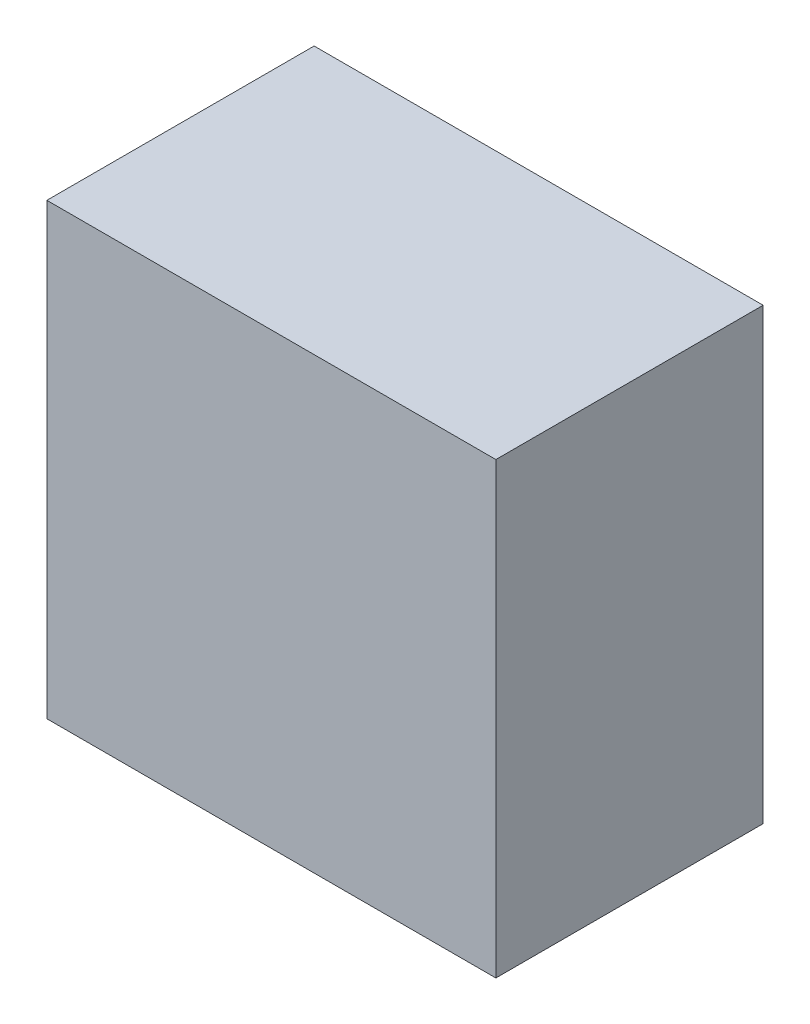
SolidWorks part; units mm, degrees
ref_plane "Plano frontal" through (0, 0, 0) normal (0, 0, 1) x (1, 0, 0)
ref_plane "Plano superior" through (0, 0, 0) normal (0, 1, 0) x (1, 0, 0)
ref_plane "Plano direito" through (0, 0, 0) normal (1, 0, 0) x (0, 0, -1)
sketch "Esboço1" plane through (0, 0, 0) normal (0, 0, 1) x (1, 0, 0)
  line L1 (-21, -21) -> (21, -21)
  line L2 (-21, -21) -> (-21, 21)
  line L3 (-21, 21) -> (21, 21)
  line L4 (21, -21) -> (21, 21)
  line L5 (-21, -21) -> (21, 21) construction
  line L6 (-21, 21) -> (21, -21) construction
  point P0 (0, 0)
  dimension "D1" = 42
  dimension "D2" = 42
extrude "Ressalto-extrusão1" add sketch "Esboço1" along normal blind 25
